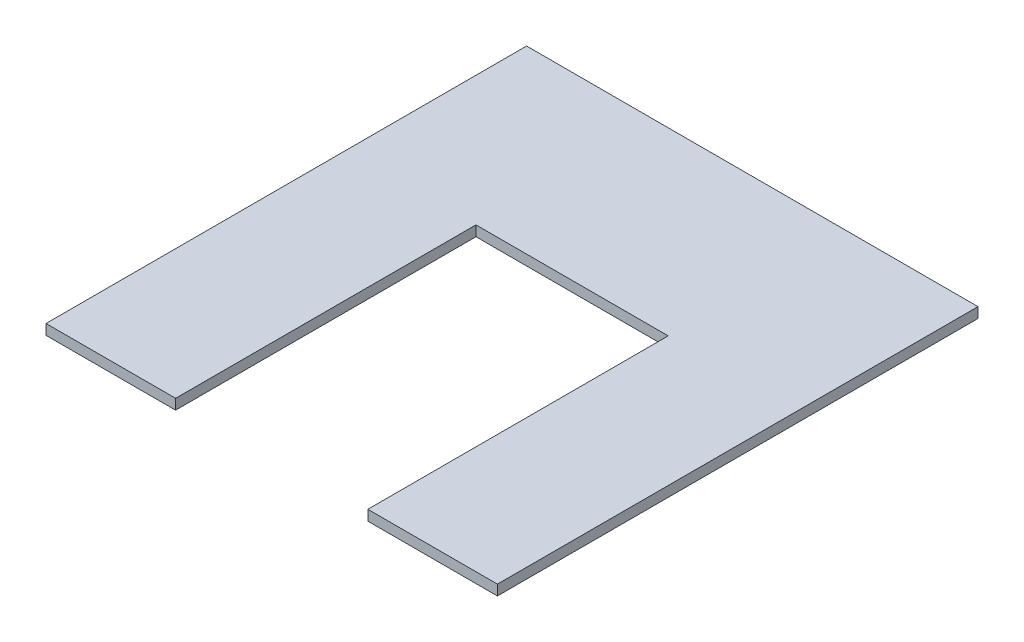
SolidWorks part; units mm, degrees
ref_plane "Front Plane" through (0, 0, 0) normal (0, 0, 1) x (1, 0, 0)
ref_plane "Top Plane" through (0, 0, 0) normal (0, 1, 0) x (1, 0, 0)
ref_plane "Right Plane" through (0, 0, 0) normal (1, 0, 0) x (0, 0, -1)
sketch "Sketch2" plane through (0, 0, 0) normal (0, 1, 0) x (1, 0, 0)
  line L0 (22.1493, 128.939) -> (22.1493, -151.061)
  line L1 (22.1493, 128.939) -> (285.1493, 128.939)
  line L2 (285.1493, 128.939) -> (285.1493, -151.061)
  line L3 (22.1493, -151.061) -> (97.6493, -151.061)
  line L4 (97.6493, -151.061) -> (97.6493, 23.939)
  line L5 (285.1493, -151.061) -> (209.6493, -151.061)
  line L6 (209.6493, -151.061) -> (209.6493, 23.939)
  line L7 (209.6493, 23.939) -> (97.6493, 23.939)
extrude "Boss-Extrude2" add sketch "Sketch2" along normal blind 6
